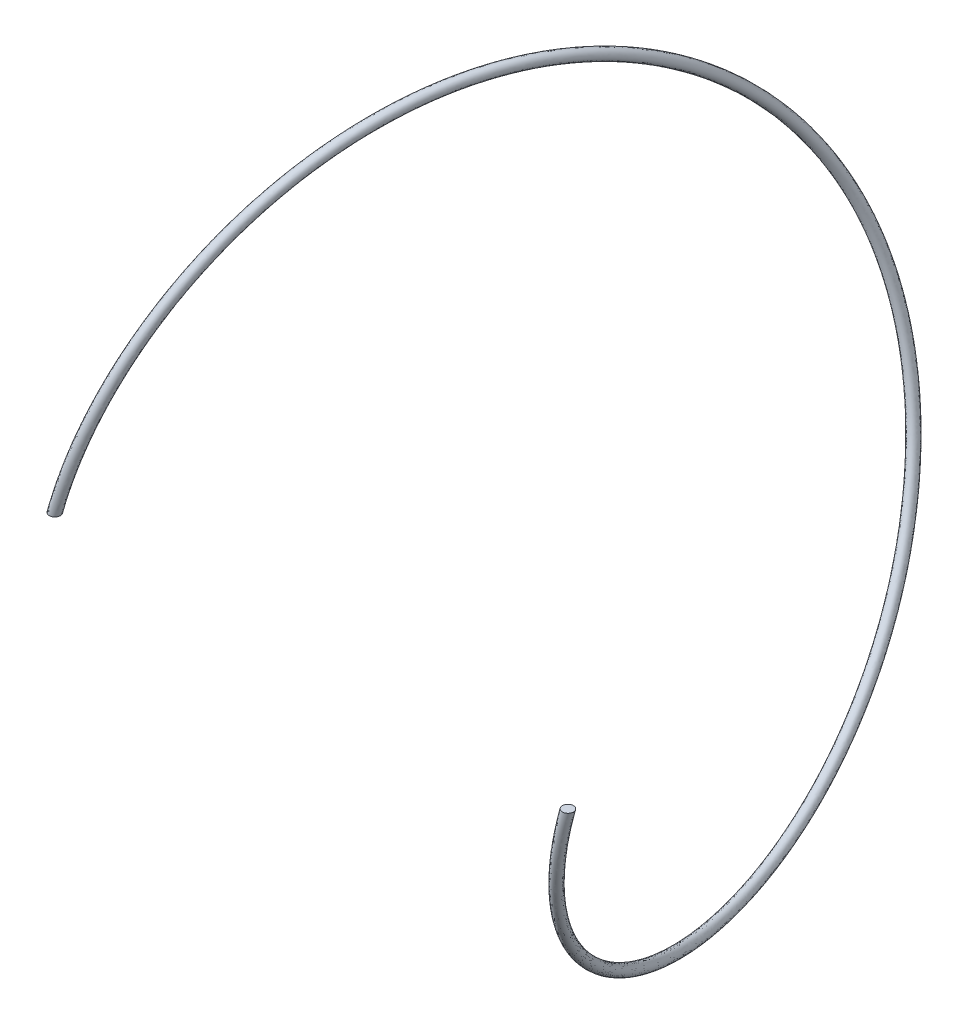
SolidWorks part; units mm, degrees
ref_plane "Спереди" through (0, 0, 0) normal (0, 0, 1) x (1, 0, 0)
ref_plane "Сверху" through (0, 0, 0) normal (0, 1, 0) x (1, 0, 0)
ref_plane "Справа" through (0, 0, 0) normal (1, 0, 0) x (0, 0, -1)
sketch "Эскиз1" plane through (0, 0, 0) normal (1, 0, 0) x (0, 0, -1)
  circle A0 centre (0, 0) radius 40
curve "Спираль1" pitch 69.5 height 69.5 turns 1
sketch "Эскиз2" plane through (0, 0, 0) normal (0, 1, 0) x (1, 0, 0)
  circle A0 centre (0, -40) radius 0.75
  spline S0 degree 3 poles (0, -40) (0.8258, -40) (2.4829, -39.3258) (4.9641, -36.3425) (7.4465, -31.5368) (9.9286, -25.1498) (12.4107, -17.5016) (14.8929, -8.9759) (17.375, 0) (19.8571, 8.9759) (22.3393, 17.5016) (24.8214, 25.1498) (27.3036, 31.5368) (29.7857, 36.3425) (32.2679, 39.3258) (34.75, 40.3371) (37.2321, 39.3258) (39.7143, 36.3425) (42.1964, 31.5368) (44.6786, 25.1498) (47.1607, 17.5016) (49.6429, 8.9759) (52.125, 0) (54.6071, -8.9759) (57.0893, -17.5016) (59.5714, -25.1498) (62.0535, -31.5368) (64.5359, -36.3425) (67.0171, -39.3258) (68.6742, -40) (69.5, -40) knots 0 0 0 0 0.035714 0.071429 0.107143 0.142857 0.178571 0.214286 0.25 0.285714 0.321429 0.357143 0.392857 0.428571 0.464286 0.5 0.535714 0.571429 0.607143 0.642857 0.678571 0.714286 0.75 0.785714 0.821429 0.857143 0.892857 0.928571 0.964286 1 1 1 1 construction
  point P4 (0, -40)
  dimension "D1" = 1.5
sweep "По траектории1" add profiles "Эскиз2" path "Спираль1"
